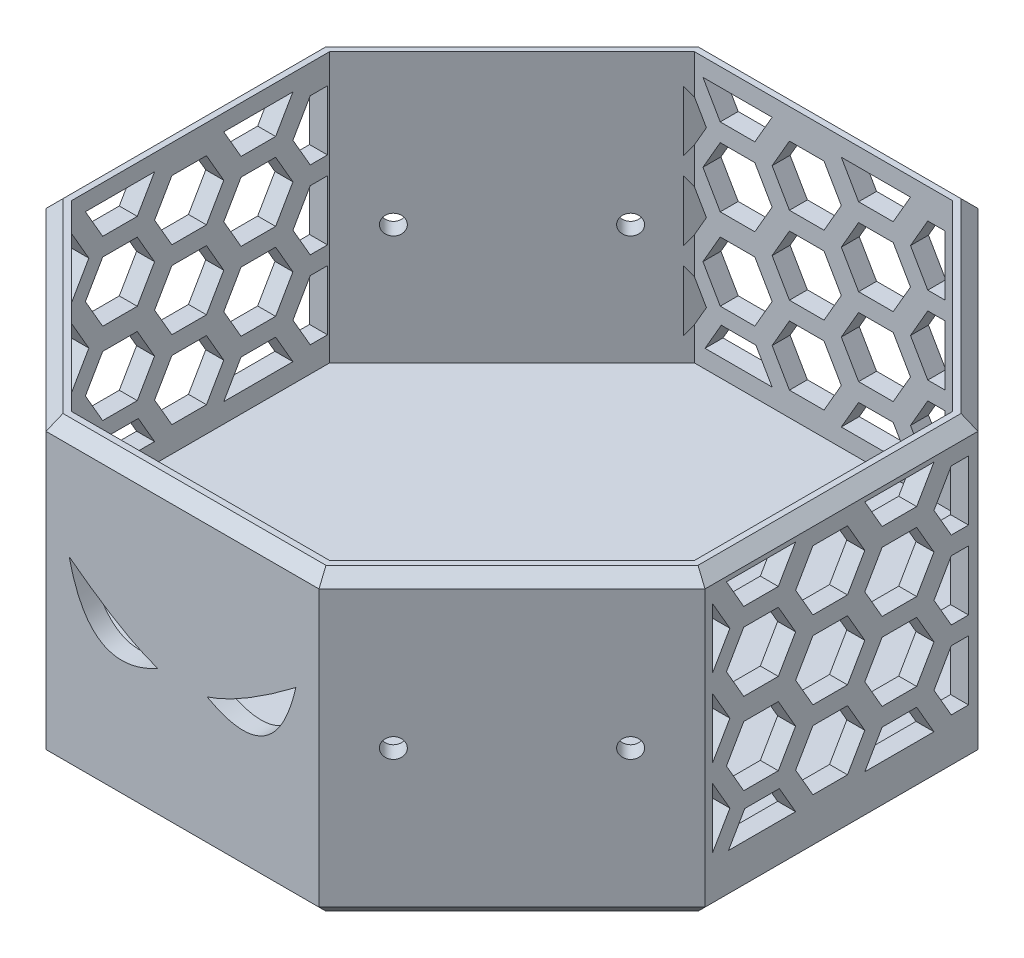
SolidWorks part; units mm, degrees
ref_plane "Plano frontal" through (0, 0, 0) normal (0, 0, 1) x (1, 0, 0)
ref_plane "Plano superior" through (0, 0, 0) normal (0, 1, 0) x (1, 0, 0)
ref_plane "Plano direito" through (0, 0, 0) normal (1, 0, 0) x (0, 0, -1)
sketch "Esboço1" plane through (0, 0, 0) normal (0, 1, 0) x (1, 0, 0)
  line L24 (55, -22.7817) -> (55, 22.7817)
  line L37 (22.7817, 55) -> (-22.7817, 55)
  line L38 (-22.7817, 55) -> (-55, 22.7817)
  line L39 (-55, 22.7817) -> (-55, -22.7817)
  line L40 (-55, -22.7817) -> (-22.7817, -55)
  line L41 (-22.7817, -55) -> (22.7817, -55)
  line L42 (22.7817, -55) -> (55, -22.7817)
  line L43 (55, 22.7817) -> (22.7817, 55)
  circle A0 centre (0, 0) radius 55 construction
  point P1 (-55, 0)
  dimension "D1" = 110
extrude "Ressalto-extrusão1" add sketch "Esboço1" along normal blind 50
sketch "Esboço2" plane through (0, 50, 0) normal (0, 1, 0) x (1, 0, 0)
  line L0 (55, 22.7817) -> (22.7817, 55) construction
  line L1 (52, 21.5391) -> (21.5391, 52)
  line L2 (21.5391, 52) -> (-21.5391, 52)
  line L3 (-21.5391, 52) -> (-52, 21.5391)
  line L4 (-52, 21.5391) -> (-52, -21.5391)
  line L5 (-52, -21.5391) -> (-21.5391, -52)
  line L6 (-21.5391, -52) -> (21.5391, -52)
  line L7 (21.5391, -52) -> (52, -21.5391)
  line L8 (52, -21.5391) -> (52, 21.5391)
  circle A0 centre (0, 0) radius 52 construction
  point P1 (-52, 0)
  dimension "D1" = 3
extrude "Corte-extrusão2" cut sketch "Esboço2" against normal blind 45
sketch "Esboço14" plane through (-38.8909, 0, 38.8909) normal (-0.7071, 0, 0.7071) x (0.7071, 0, 0.7071)
  line L0 (-14, 25) -> (14, 25) construction
  line L1 (-22.7817, 0) -> (22.7817, 0) construction
  circle A0 centre (-14, 25) radius 1.65
  circle A1 centre (14, 25) radius 1.65
  point P4 (0, 25)
  dimension "D3" = 3.3
  dimension "D1" = 28
  dimension "D2" = 25
extrude "Corte-extrusão6" cut sketch "Esboço14" against normal through all
sketch "Esboço15" plane through (-38.8909, 0, -38.8909) normal (-0.7071, 0, -0.7071) x (-0.7071, 0, 0.7071)
  line L0 (-14, 25) -> (14, 25) construction
  line L1 (-22.7817, 0) -> (22.7817, 0) construction
  circle A0 centre (-14, 25) radius 1.65
  circle A1 centre (14, 25) radius 1.65
  point P4 (0, 25)
  dimension "D1" = 3.3
  dimension "D2" = 28
  dimension "D3" = 25
extrude "Corte-extrusão7" cut sketch "Esboço15" against normal through all
chamfer "Chanfro1" distance 2 angle 45 16 edges at (-55, 0, 0) (-38.8909, 0, -38.8909) (0, 0, -55) (38.8909, 0, -38.8909) (55, 0, 0) (38.8909, 0, 38.8909) (0, 0, 55) (-38.8909, 0, 38.8909) (38.8909, 50, 38.8909) (55, 50, 0) (38.8909, 50, -38.8909) (0, 50, -55) (-38.8909, 50, -38.8909) (-55, 50, 0) (-38.8909, 50, 38.8909) (0, 50, 55)
sketch "Esboço11" plane through (-55, 0, 0) normal (-1, 0, 0) x (0, 0, 1)
  line L12 (18.862, 8.2396) -> (16.1485, 12.9395)
  line L15 (7.6615, 27.2396) -> (4.7748, 32.2396)
  line L53 (4.7748, 32.2396) -> (-0.9987, 32.2396)
  line L169 (-0.9987, 32.2396) -> (-3.8855, 27.2396)
  line L170 (16.1485, 12.9395) -> (10.375, 12.9395)
  line L171 (10.375, 12.9395) -> (7.6615, 8.2396)
  line L172 (-3.8855, 27.2396) -> (-0.9987, 22.2396)
  line L173 (-0.9987, 22.2396) -> (4.7748, 22.2396)
  line L174 (4.7748, 22.2396) -> (7.6615, 27.2396)
  line L175 (-3.8855, 21.2396) -> (-6.7722, 26.2396)
  line L176 (-6.7722, 26.2396) -> (-12.5457, 26.2396)
  line L177 (-12.5457, 26.2396) -> (-15.4325, 21.2396)
  line L178 (-15.4325, 21.2396) -> (-12.5457, 16.2396)
  line L179 (-12.5457, 16.2396) -> (-6.7722, 16.2396)
  line L180 (-6.7722, 16.2396) -> (-3.8855, 21.2396)
  line L181 (7.6615, 40.2396) -> (4.7748, 45.2396)
  line L182 (4.7748, 45.2396) -> (-0.9987, 45.2396)
  line L183 (-0.9987, 45.2396) -> (-3.8855, 40.2396)
  line L184 (-3.8855, 40.2396) -> (-0.9987, 35.2396)
  line L185 (-0.9987, 35.2396) -> (4.7748, 35.2396)
  line L186 (4.7748, 35.2396) -> (7.6615, 40.2396)
  line L187 (7.6615, 14.2396) -> (4.7748, 19.2396)
  line L188 (4.7748, 19.2396) -> (-0.9987, 19.2396)
  line L189 (-0.9987, 19.2396) -> (-3.8855, 14.2396)
  line L190 (-3.8855, 14.2396) -> (-0.9987, 9.2396)
  line L191 (-0.9987, 9.2396) -> (4.7748, 9.2396)
  line L192 (4.7748, 9.2396) -> (7.6615, 14.2396)
  line L193 (7.6615, 8.2396) -> (18.862, 8.2396)
  line L194 (-15.4325, 8.2396) -> (-3.8855, 8.2396)
  line L195 (-3.8855, 8.2396) -> (-6.7722, 13.2396)
  line L196 (-6.7722, 13.2396) -> (-12.5457, 13.2396)
  line L197 (-12.5457, 13.2396) -> (-15.4325, 8.2396)
  line L198 (-15.4325, 47.2396) -> (-3.8855, 47.2396)
  line L199 (-3.8855, 34.2396) -> (-6.7722, 39.2396)
  line L200 (-6.7722, 39.2396) -> (-12.5457, 39.2396)
  line L201 (-12.5457, 39.2396) -> (-15.4325, 34.2396)
  line L202 (-15.4325, 34.2396) -> (-12.5457, 29.2396)
  line L203 (-12.5457, 29.2396) -> (-6.7722, 29.2396)
  line L204 (-6.7722, 29.2396) -> (-3.8855, 34.2396)
  line L205 (-15.4325, 47.2396) -> (-12.5457, 42.2396)
  line L206 (-12.5457, 42.2396) -> (-6.7722, 42.2396)
  line L207 (-6.7722, 42.2396) -> (-3.8855, 47.2396)
  line L208 (-21.206, 45.2396) -> (-21.206, 9.2396) construction
  line L209 (-21.206, 45.2396) -> (-21.206, 35.2396)
  line L210 (-15.4325, 40.2396) -> (-18.3192, 45.2396)
  line L211 (-18.3192, 45.2396) -> (-21.206, 45.2396)
  line L212 (-21.206, 35.2396) -> (-18.3192, 35.2396)
  line L213 (-18.3192, 35.2396) -> (-15.4325, 40.2396)
  line L214 (-15.4325, 27.2396) -> (-18.3192, 32.2396)
  line L215 (-18.3192, 32.2396) -> (-21.206, 32.2396)
  line L216 (-21.206, 32.2396) -> (-21.206, 22.2396)
  line L217 (-21.206, 22.2396) -> (-18.3192, 22.2396)
  line L218 (-18.3192, 22.2396) -> (-15.4325, 27.2396)
  line L219 (-15.4325, 14.2396) -> (-18.3192, 19.2396)
  line L220 (-18.3192, 19.2396) -> (-21.206, 19.2396)
  line L221 (-21.206, 19.2396) -> (-21.206, 9.2396)
  line L222 (-21.206, 9.2396) -> (-18.3192, 9.2396)
  line L223 (-18.3192, 9.2396) -> (-15.4325, 14.2396)
  line L224 (19.2085, 34.2396) -> (16.3218, 39.2396)
  line L225 (16.3218, 39.2396) -> (10.5483, 39.2396)
  line L226 (10.5483, 39.2396) -> (7.6615, 34.2396)
  line L227 (7.6615, 34.2396) -> (10.5483, 29.2396)
  line L228 (10.5483, 29.2396) -> (16.3218, 29.2396)
  line L229 (16.3218, 29.2396) -> (19.2085, 34.2396)
  line L230 (7.6615, 47.2396) -> (10.5483, 42.2396)
  line L231 (10.5483, 42.2396) -> (16.3218, 42.2396)
  line L232 (16.3218, 42.2396) -> (19.2085, 47.2396)
  line L233 (7.6615, 47.2396) -> (19.2085, 47.2396)
  line L234 (21.5179, 45.2396) -> (21.5179, 35.2396)
  line L235 (19.2085, 20.6028) -> (16.3218, 25.6028)
  line L236 (16.3218, 25.6028) -> (10.5483, 25.6028)
  line L237 (10.5483, 25.6028) -> (7.6615, 20.6028)
  line L238 (7.6615, 20.6028) -> (10.5483, 15.6028)
  line L239 (10.5483, 15.6028) -> (16.3218, 15.6028)
  line L240 (16.3218, 15.6028) -> (19.2085, 20.6028)
  line L241 (21.5179, 45.2396) -> (18.6312, 40.2396)
  line L242 (18.6312, 40.2396) -> (21.5179, 35.2396)
  line L243 (21.5179, 45.2396) -> (21.5179, 8.2396) construction
  line L244 (21.5179, 32.2396) -> (21.5179, 22.2396)
  line L245 (18.6312, 27.2396) -> (21.5179, 22.2396)
  line L246 (21.5179, 32.2396) -> (18.6312, 27.2396)
  line L247 (21.5179, 19.2396) -> (21.5179, 9.2396)
  line L248 (18.6312, 14.2396) -> (21.5179, 9.2396)
  line L249 (21.5179, 19.2396) -> (18.6312, 14.2396)
  arc A0 (18.2528, 8.2396) -> (8.2708, 8.2396) centre (13.2618, 7.9395) ccw construction
  circle A2 centre (1.888, 27.2396) radius 5 construction
  circle A3 centre (-9.659, 21.2396) radius 5 construction
  circle A4 centre (1.888, 40.2396) radius 5 construction
  circle A5 centre (1.888, 14.2396) radius 5 construction
  arc A6 (-4.659, 8.2396) -> (-14.659, 8.2396) centre (-9.659, 8.2396) ccw construction
  circle A7 centre (-9.659, 34.2396) radius 5 construction
  arc A8 (-14.659, 47.2396) -> (-4.659, 47.2396) centre (-9.659, 47.2396) ccw construction
  arc A9 (-21.206, 35.2396) -> (-21.206, 45.2396) centre (-21.206, 40.2396) ccw construction
  circle A10 centre (13.435, 34.2396) radius 5 construction
  arc A11 (8.435, 47.2396) -> (18.435, 47.2396) centre (13.435, 47.2396) ccw construction
  circle A12 centre (13.435, 20.6028) radius 5 construction
  arc A13 (21.5179, 44.3221) -> (21.5179, 36.1571) centre (24.4047, 40.2396) ccw construction
  point P52 (13.2618, 8.2396)
  dimension "D1" = 10
  dimension "D2" = 10
  dimension "D3" = 10
  dimension "D4" = 10
  dimension "D6" = 10
  dimension "D9" = 10
  dimension "D12" = 10
  dimension "D15" = 10
  dimension "D5" = 3
  dimension "D7" = 3
  dimension "D8" = 3
  dimension "D10" = 3
  dimension "D11" = 3
  dimension "D13" = 3
  dimension "D14" = 3
  dimension "D16" = 3
  dimension "D17" = 3
  dimension "D18" = 3
  dimension "D19" = 3
extrude "Corte-extrusão3" cut sketch "Esboço11" against normal through all
sketch "Esboço12" plane through (0, 0, -55) normal (0, 0, -1) x (-1, 0, 0)
  line L0 (22.7817, 48) -> (-22.7817, 48) construction
  line L1 (-22.7817, 2) -> (22.7817, 2) construction
  line L2 (22.7817, 48) -> (22.7817, 2) construction
  line L3 (19.7817, 8) -> (17.0682, 12.6999)
  line L4 (8.5812, 27) -> (5.6945, 32)
  line L5 (5.6945, 32) -> (-0.079, 32)
  line L6 (-0.079, 32) -> (-2.9658, 27)
  line L127 (17.0682, 12.6999) -> (11.2947, 12.6999)
  line L128 (11.2947, 12.6999) -> (8.5812, 8)
  line L132 (-2.9658, 27) -> (-0.079, 22)
  line L133 (-0.079, 22) -> (5.6945, 22)
  line L134 (5.6945, 22) -> (8.5812, 27)
  line L135 (-2.9658, 21) -> (-5.8525, 26)
  line L136 (-5.8525, 26) -> (-11.626, 26)
  line L137 (-11.626, 26) -> (-14.5128, 21)
  line L138 (-14.5128, 21) -> (-11.626, 16)
  line L139 (-11.626, 16) -> (-5.8525, 16)
  line L140 (-5.8525, 16) -> (-2.9658, 21)
  line L147 (8.5812, 40) -> (5.6945, 45)
  line L148 (5.6945, 45) -> (-0.079, 45)
  line L149 (-0.079, 45) -> (-2.9658, 40)
  line L150 (-2.9658, 40) -> (-0.079, 35)
  line L151 (-0.079, 35) -> (5.6945, 35)
  line L152 (5.6945, 35) -> (8.5812, 40)
  line L153 (8.5812, 14) -> (5.6945, 19)
  line L154 (5.6945, 19) -> (-0.079, 19)
  line L155 (-0.079, 19) -> (-2.9658, 14)
  line L156 (-2.9658, 14) -> (-0.079, 9)
  line L157 (-0.079, 9) -> (5.6945, 9)
  line L158 (5.6945, 9) -> (8.5812, 14)
  line L159 (8.5812, 8) -> (19.7817, 8)
  line L160 (-14.5128, 8) -> (-2.9658, 8)
  line L161 (14.1815, 2.6999) -> (17.0682, 2.6999) [skipped]
  line L162 (18.5116, 5.1999) -> (19.955, 7.6999) [skipped]
  line L163 (8.408, 7.6999) -> (11.2947, 2.6999) [skipped]
  line L164 (-2.9658, 8) -> (-5.8525, 13)
  line L165 (-5.8525, 13) -> (-11.626, 13)
  line L166 (-11.626, 13) -> (-14.5128, 8)
  line L170 (-14.5128, 47) -> (-2.9658, 47)
  line L171 (-3.361, 7.3154) -> (-1.9177, 9.8154) [skipped]
  line L172 (-11.626, 3) -> (-8.7393, 3) [skipped]
  line L173 (-14.5128, 8) -> (-13.0694, 5.5) [skipped]
  line L174 (-2.9658, 34) -> (-5.8525, 39)
  line L175 (-5.8525, 39) -> (-11.626, 39)
  line L176 (-11.626, 39) -> (-14.5128, 34)
  line L177 (-14.5128, 34) -> (-11.626, 29)
  line L178 (-11.626, 29) -> (-5.8525, 29)
  line L179 (-5.8525, 29) -> (-2.9658, 34)
  line L183 (-14.5128, 47) -> (-11.626, 42)
  line L184 (-11.626, 42) -> (-5.8525, 42)
  line L185 (-5.8525, 42) -> (-2.9658, 47)
  line L186 (-20.2863, 45) -> (-20.2863, 9) construction
  line L187 (-8.7393, 52) -> (-11.626, 52) [skipped]
  line L188 (-13.0694, 49.5) -> (-14.5128, 47) [skipped]
  line L189 (-4.4091, 49.5) -> (-5.8525, 52) [skipped]
  line L190 (-20.2863, 45) -> (-20.2863, 35)
  line L191 (-14.5128, 40) -> (-17.3995, 45)
  line L192 (-17.3995, 45) -> (-20.2863, 45)
  line L195 (-20.2863, 35) -> (-17.3995, 35)
  line L196 (-17.3995, 35) -> (-14.5128, 40)
  line L197 (-14.5128, 27) -> (-17.3995, 32)
  line L198 (-24.6164, 42.5) -> (-26.0598, 40) [skipped]
  line L199 (-24.6164, 37.5) -> (-23.173, 35) [skipped]
  line L200 (-17.3995, 32) -> (-20.2863, 32)
  line L201 (-20.2863, 32) -> (-20.2863, 22)
  line L202 (-20.2863, 22) -> (-17.3995, 22)
  line L203 (-17.3995, 22) -> (-14.5128, 27)
  line L204 (-14.5128, 14) -> (-17.3995, 19)
  line L205 (-17.3995, 19) -> (-20.2863, 19)
  line L206 (-20.2863, 19) -> (-20.2863, 9)
  line L207 (-20.2863, 9) -> (-17.3995, 9)
  line L208 (-17.3995, 9) -> (-14.5128, 14)
  line L210 (20.1282, 34) -> (17.2415, 39)
  line L211 (17.2415, 39) -> (11.468, 39)
  line L212 (11.468, 39) -> (8.5812, 34)
  line L213 (8.5812, 34) -> (11.468, 29)
  line L214 (11.468, 29) -> (17.2415, 29)
  line L215 (17.2415, 29) -> (20.1282, 34)
  line L220 (8.5812, 47) -> (11.468, 42)
  line L221 (11.468, 42) -> (17.2415, 42)
  line L222 (17.2415, 42) -> (20.1282, 47)
  line L223 (8.5812, 47) -> (20.1282, 47)
  line L224 (22.4376, 45) -> (22.4376, 35)
  line L225 (14.3547, 52) -> (11.468, 52) [skipped]
  line L226 (10.0246, 49.5) -> (8.5812, 47) [skipped]
  line L227 (18.6849, 49.5) -> (17.2415, 52) [skipped]
  line L228 (20.1282, 20.3632) -> (17.2415, 25.3632)
  line L229 (17.2415, 25.3632) -> (11.468, 25.3632)
  line L230 (11.468, 25.3632) -> (8.5812, 20.3632)
  line L231 (8.5812, 20.3632) -> (11.468, 15.3632)
  line L232 (11.468, 15.3632) -> (17.2415, 15.3632)
  line L233 (17.2415, 15.3632) -> (20.1282, 20.3632)
  line L236 (22.4376, 45) -> (19.5509, 40)
  line L237 (19.5509, 40) -> (22.4376, 35)
  line L240 (22.4376, 45) -> (22.4376, 8) construction
  line L241 (31.0979, 40) -> (29.6545, 42.5) [skipped]
  line L242 (28.2112, 35) -> (29.6545, 37.5) [skipped]
  line L243 (22.4376, 35) -> (25.3244, 35) [skipped]
  line L244 (25.3244, 45) -> (22.4376, 45) [skipped]
  line L245 (22.4376, 32) -> (22.4376, 22)
  line L246 (19.5509, 27) -> (22.4376, 22)
  line L247 (22.4376, 32) -> (19.5509, 27)
  line L248 (22.4376, 19) -> (22.4376, 9)
  line L249 (19.5509, 14) -> (22.4376, 9)
  line L250 (22.4376, 19) -> (19.5509, 14)
  arc A0 (19.1725, 8) -> (9.1905, 8) centre (14.1815, 7.6999) ccw construction
  circle A1 centre (2.8077, 27) radius 5 construction
  circle A2 centre (-8.7393, 21) radius 5 construction
  circle A3 centre (2.8077, 40) radius 5 construction
  circle A4 centre (2.8077, 14) radius 5 construction
  arc A5 (-3.7393, 8) -> (-13.7393, 8) centre (-8.7393, 8) ccw construction
  circle A6 centre (-8.7393, 34) radius 5 construction
  arc A7 (-13.7393, 47) -> (-3.7393, 47) centre (-8.7393, 47) ccw construction
  arc A8 (-20.2863, 35) -> (-20.2863, 45) centre (-20.2863, 40) ccw construction
  circle A9 centre (14.3547, 34) radius 5 construction
  arc A10 (9.3547, 47) -> (19.3547, 47) centre (14.3547, 47) ccw construction
  circle A11 centre (14.3547, 20.3632) radius 5 construction
  arc A12 (22.4376, 44.0825) -> (22.4376, 35.9175) centre (25.3244, 40) ccw construction
  point P63 (14.1815, 8)
  dimension "D3" = 3
  dimension "D2" = 10
  dimension "D4" = 10
  dimension "D6" = 10
  dimension "D8" = 10
  dimension "D10" = 10
  dimension "D13" = 10
  dimension "D16" = 10
  dimension "D19" = 10
  dimension "D20" = 3
  dimension "D5" = 3
  dimension "D7" = 3
  dimension "D9" = 3
  dimension "D11" = 3
  dimension "D12" = 3
  dimension "D14" = 6
  dimension "D15" = 3
  dimension "D17" = 3
  dimension "D18" = 3
  dimension "D22" = 3
  dimension "D23" = 3
  dimension "D24" = 3
  dimension "D21" = 3
  dimension "D25" = 3
extrude "Corte-extrusão4" cut sketch "Esboço12" against normal blind 10
sketch "Esboço13" plane through (0, 0, 55) normal (0, 0, 1) x (1, 0, 0)
  line L0 (0, 2) -> (0, 48) construction
  line L1 (-22.7817, 2) -> (22.7817, 2) construction
  line L2 (22.7817, 48) -> (-22.7817, 48) construction
  spline S0 degree 2 poles (-18.9179, 31.8128) (-9.7909, 24.9037) (-4.1074, 23.0506) knots 0 0 0 1 1 1
  spline S1 degree 2 poles (-18.9179, 31.8128) (-15.5168, 16.8069) (-4.1074, 23.0506) knots 0 0 0 1 1 1
  spline S2 degree 2 poles (18.9179, 31.8128) (9.7909, 24.9037) (4.1074, 23.0506) knots 0 0 0 1 1 1
  spline S3 degree 2 poles (18.9179, 31.8128) (15.5168, 16.8069) (4.1074, 23.0506) knots 0 0 0 1 1 1
extrude "Corte-extrusão5" cut sketch "Esboço13" against normal blind 10
